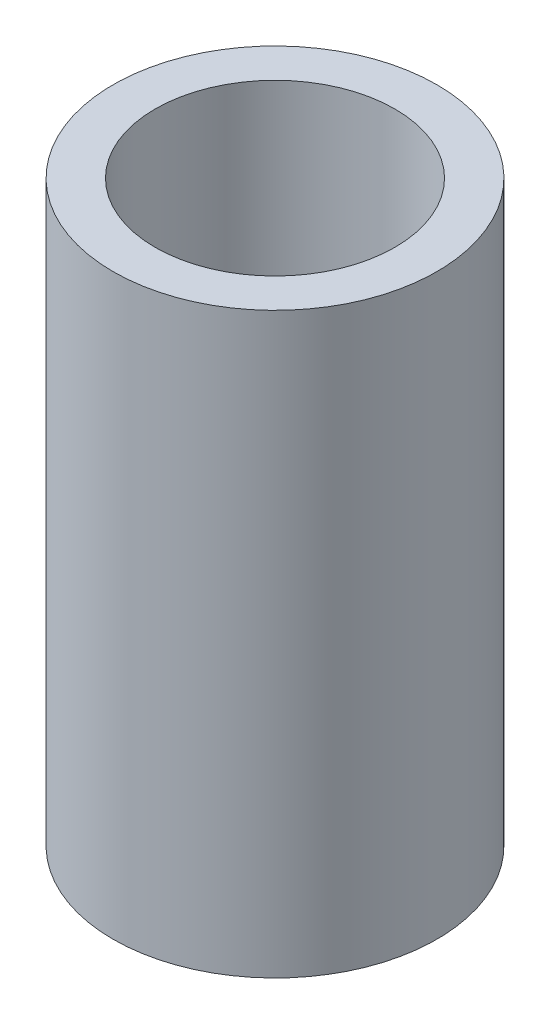
SolidWorks part; units mm, degrees
material "PVC Rigid"
ref_plane "Front Plane" through (0, 0, 0) normal (0, 0, 1) x (1, 0, 0)
ref_plane "Top Plane" through (0, 0, 0) normal (0, 1, 0) x (1, 0, 0)
ref_plane "Right Plane" through (0, 0, 0) normal (1, 0, 0) x (0, 0, -1)
sketch "Sketch1" plane through (0, 0, 0) normal (0, 1, 0) x (1, 0, 0)
  circle A0 centre (0, 0) radius 10.668
  circle A1 centre (0, 0) radius 7.8994
  dimension "D1" = 21.336
  dimension "D2" = 15.7988
  dimension "D3" = 2.7686
extrude "Boss-Extrude1" add sketch "Sketch1" along normal blind 38.1
